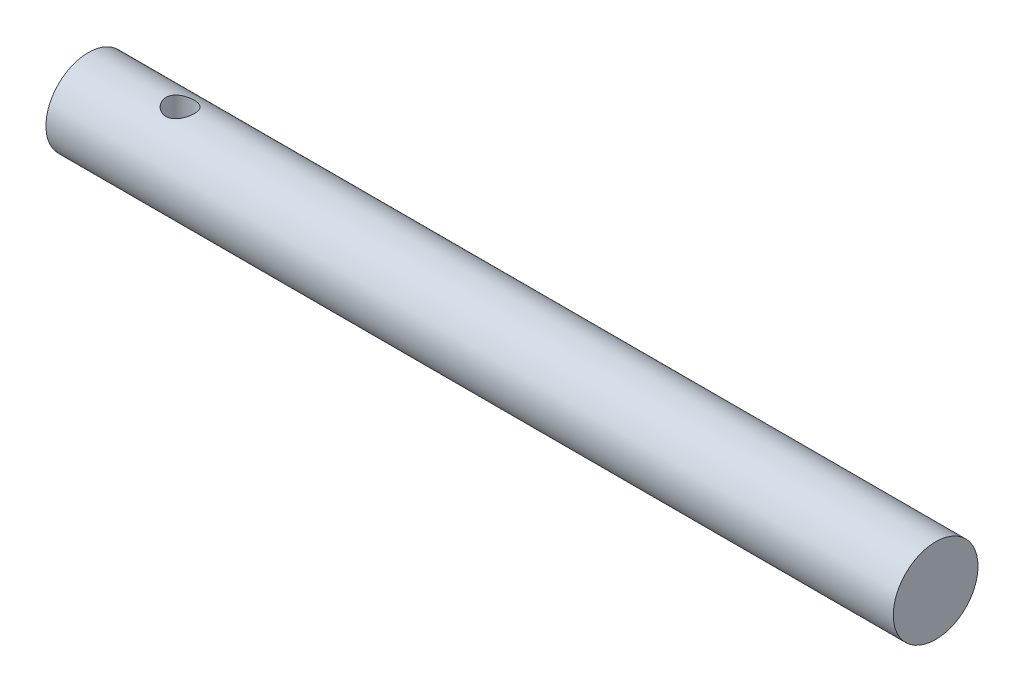
SolidWorks part; units mm, degrees
other "Preload Screw M6x1 RH"
ref_plane "Front Plane" through (0, 0, 0) normal (0, 0, 1) x (1, 0, 0)
ref_plane "Top Plane" through (0, 0, 0) normal (0, 1, 0) x (1, 0, 0)
ref_plane "Right Plane" through (0, 0, 0) normal (1, 0, 0) x (0, 0, -1)
sketch3d "M6 threaded stock envelope sketch datum points"
  point P0 (2.5, -29, -19.5)
  point P1 (2.5, -19, -19.5)
  point P2 (2.5, -29, -9.5)
ref_plane "M6 threaded stock envelope sketch plane" through (2.5, 0, 0) normal (1, 0, 0) x (0, 0, -1)
sketch "M6 threaded stock envelope sketch" plane through (2.5, 0, 0) normal (1, 0, 0) x (0, 0, -1)
  circle A0 centre (19.5, -29) radius 3
extrude "M6 threaded stock envelope" add sketch "M6 threaded stock envelope sketch" along normal blind 60 separate body
sketch3d "Coupling pin cross hole sketch datum points"
  point P0 (9, -33, -19.5)
  point P1 (19, -33, -19.5)
  point P2 (9, -33, -29.5)
ref_plane "Coupling pin cross hole sketch plane" through (0, -33, 0) normal (0, 1, 0) x (1, 0, 0)
sketch "Coupling pin cross hole sketch" plane through (0, -33, 0) normal (0, 1, 0) x (1, 0, 0)
  circle A0 centre (9, 19.5) radius 1
extrude "Coupling pin cross hole" cut sketch "Coupling pin cross hole sketch" along normal blind 8
